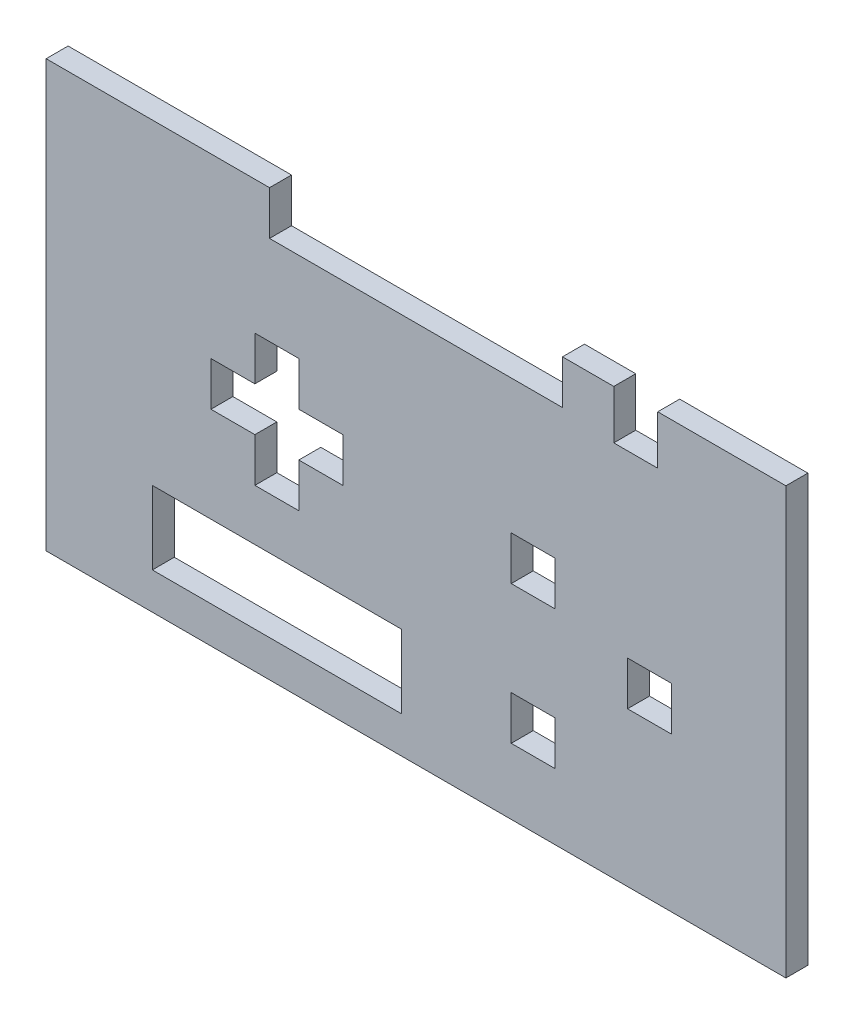
SolidWorks part; units mm, degrees
ref_plane "Front Plane" through (0, 0, 0) normal (0, 0, 1) x (1, 0, 0)
ref_plane "Top Plane" through (0, 0, 0) normal (0, 1, 0) x (1, 0, 0)
ref_plane "Right Plane" through (0, 0, 0) normal (1, 0, 0) x (0, 0, -1)
sketch "Sketch1" plane through (0, 0, 0) normal (0, 0, 1) x (1, 0, 0)
  line L0 (-50.5, -7.4) -> (-50.5, -65.6)
  line L1 (-50.5, -65.6) -> (50.5, -65.6)
  line L3 (-50.5, -7.4) -> (50.5, -7.4)
  line L4 (50.5, -65.6) -> (50.5, -7.4)
  point P0 (0, 0)
  dimension "D1" = 101
  dimension "D2" = 58.2
  dimension "D3" = 50.5
  dimension "D4" = 7.4
extrude "Boss-Extrude1" add sketch "Sketch1" along normal mid plane 3 contours L3 L4 L1 L0
sketch "Sketch2" plane through (0, 0, 1.5) normal (0, 0, 1) x (1, 0, 0)
  line L0 (50.5, -65.6) -> (50.5, -7.4) construction
  line L1 (13, -37.7132) -> (19, -37.7132)
  line L2 (13, -37.7132) -> (13, -31.7132)
  line L3 (13, -31.7132) -> (19, -31.7132)
  line L6 (-50.5, -7.4) -> (50.5, -7.4) construction
  line L7 (28.8814, -44.5756) -> (34.8814, -44.5756)
  line L8 (28.8814, -44.5756) -> (28.8814, -38.5756)
  line L9 (28.8814, -38.5756) -> (34.8814, -38.5756)
  line L10 (-20, -7.4) -> (20, -7.4)
  line L12 (13, -56.6) -> (19, -56.6)
  line L13 (13, -56.6) -> (13, -50.6)
  line L14 (13, -50.6) -> (19, -50.6)
  line L15 (19, -56.6) -> (19, -50.6)
  line L16 (13, -56.6) -> (19, -50.6) construction
  line L17 (13, -50.6) -> (19, -56.6) construction
  line L18 (-50.5, -65.6) -> (50.5, -65.6) construction
  line L19 (19, -37.7132) -> (19, -31.7132)
  line L20 (13, -37.7132) -> (19, -31.7132) construction
  line L21 (13, -31.7132) -> (19, -37.7132) construction
  line L22 (34.8814, -44.5756) -> (34.8814, -38.5756)
  line L23 (-22, -43.6) -> (-16, -43.6)
  line L24 (-28, -37.6) -> (-22, -37.6)
  line L25 (-28, -37.6) -> (-28, -31.6)
  line L26 (-28, -31.6) -> (-22, -31.6)
  line L27 (-10, -37.6) -> (-10, -31.6)
  line L28 (-16, -31.6) -> (-10, -31.6)
  line L29 (-22, -31.6) -> (-22, -25.6)
  line L30 (-22, -43.6) -> (-22, -37.6)
  line L31 (-22, -25.6) -> (-16, -25.6)
  line L32 (-16, -43.6) -> (-16, -37.6)
  line L33 (-16, -37.6) -> (-10, -37.6)
  line L34 (-16, -31.6) -> (-16, -25.6)
  line L35 (28.8814, -44.5756) -> (34.8814, -38.5756) construction
  line L36 (28.8814, -38.5756) -> (34.8814, -44.5756) construction
  line L37 (27, -14.0756) -> (33, -14.0756)
  line L38 (27, -14.0756) -> (27, -6.0756)
  line L39 (27, -6.0756) -> (33, -6.0756)
  line L40 (33, -14.0756) -> (33, -6.0756)
  line L41 (27, -14.0756) -> (33, -6.0756) construction
  line L42 (27, -6.0756) -> (33, -14.0756) construction
  line L43 (-20, -7.4) -> (-20, -13.4)
  line L44 (-20, -13.4) -> (20, -13.4)
  line L45 (20, -7.4) -> (20, -13.4)
  line L46 (-50.5, -7.4) -> (-50.5, -65.6) construction
  line L47 (-50.5, -7.4) -> (-50.5, -65.6) construction
  line L49 (-36, -60.6) -> (-2, -60.6)
  line L50 (-36, -60.6) -> (-36, -50.6)
  line L51 (-36, -50.6) -> (-2, -50.6)
  line L52 (-2, -60.6) -> (-2, -50.6)
  dimension "D5" = 6
  dimension "D6" = 9
  dimension "D9" = 8
  dimension "D10" = 6
  dimension "D13" = 6
  dimension "D15" = 6
  dimension "D17" = 6
  dimension "D20" = 17.5
  dimension "D4" = 63.5
  dimension "D7" = 22
  dimension "D8" = 22.5
  dimension "D11" = 63.5
  dimension "D12" = 12.8868
  dimension "D14" = 6
  dimension "D16" = 6
  dimension "D18" = 9.8814
  dimension "D19" = 21.0244
  dimension "D21" = 6
  dimension "D22" = 24.5
  dimension "D23" = 20
  dimension "D24" = 40
  dimension "D25" = 18
  dimension "D26" = 6
  dimension "D27" = 6
  dimension "D28" = 18
  dimension "D29" = 14.5
  dimension "D30" = 5
  dimension "D31" = 6
  dimension "D32" = 6
  dimension "D33" = 10
  dimension "D34" = 34
extrude "Cut-Extrude2" cut sketch "Sketch2" against normal through all
